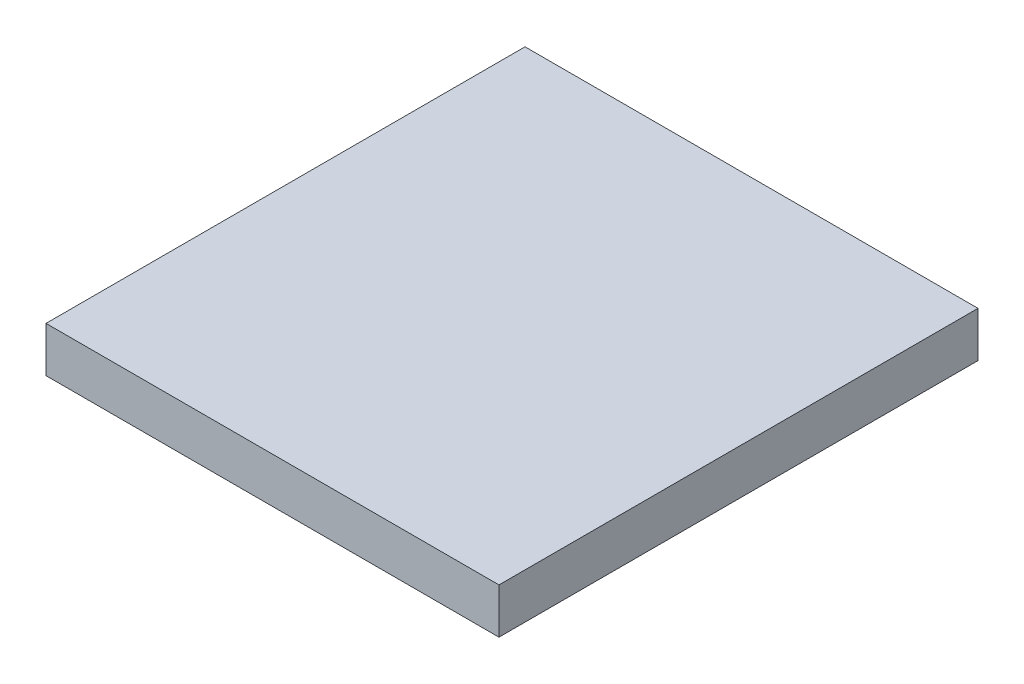
SolidWorks part; units mm, degrees
ref_plane "Front Plane" through (0, 0, 0) normal (0, 0, 1) x (1, 0, 0)
ref_plane "Top Plane" through (0, 0, 0) normal (0, 1, 0) x (1, 0, 0)
ref_plane "Right Plane" through (0, 0, 0) normal (1, 0, 0) x (0, 0, -1)
sketch "Sketch1" plane through (0, 0, 0) normal (0, 1, 0) x (1, 0, 0)
  line L1 (0, 0) -> (40, 0)
  line L2 (0, 0) -> (0, -42.3)
  line L3 (0, -42.3) -> (40, -42.3)
  line L4 (40, 0) -> (40, -42.3)
  dimension "D1" = 40
  dimension "D2" = 42.3
extrude "Boss-Extrude1" add sketch "Sketch1" along normal blind 4
